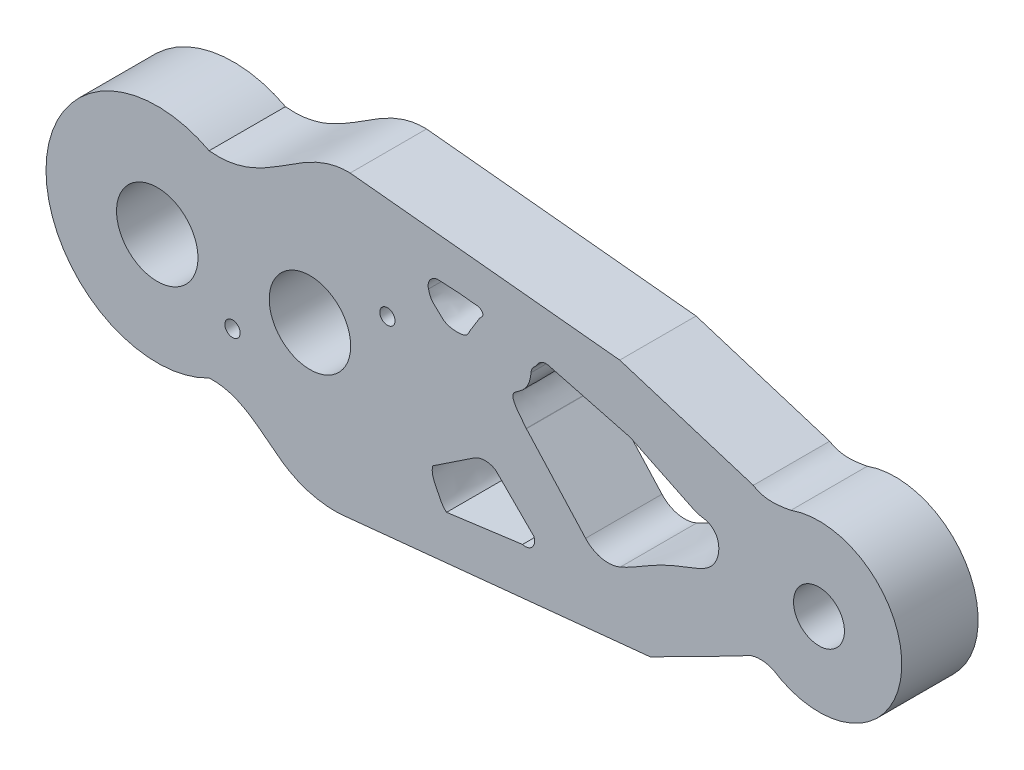
SolidWorks part; units mm, degrees
ref_plane "Front Plane" through (0, 0, 0) normal (0, 0, 1) x (1, 0, 0)
ref_plane "Top Plane" through (0, 0, 0) normal (0, 1, 0) x (1, 0, 0)
ref_plane "Right Plane" through (0, 0, 0) normal (1, 0, 0) x (0, 0, -1)
sketch "Sketch1" plane through (0, 0, 0) normal (0, 0, 1) x (1, 0, 0)
  line L0 (1.3706, 14.9583) -> (51.0041, 9.9495)
  line L1 (1.3706, -14.9583) -> (51.0041, -9.9495)
  line L2 (-15.0209, 15) -> (0, 15.021)
  line L3 (-15, -15) -> (-0.7932, -15)
  circle A0 centre (-15, 0) radius 4
  circle A1 centre (0, 0) radius 4
  circle A2 centre (50, 0) radius 2.5
  arc A4 (-15.0209, 15) -> (-15, -15) centre (-15, 0) ccw
  arc A5 (51.0041, -9.9495) -> (51.0041, 9.9495) centre (50, 0) ccw
  arc A6 (-0.7932, -15) -> (1.3706, -14.9583) centre (0, 0) ccw
  arc A7 (1.3706, 14.9583) -> (0, 15.021) centre (0, 0) ccw
  dimension "D1" = 20
  dimension "D2" = 15
  dimension "D4" = 8
  dimension "D5" = 5
  dimension "D3" = 50
  dimension "D6" = 15
extrude "Boss-Extrude1" add sketch "Sketch1" along normal mid plane 7.5
sketch "Sketch2" plane through (0, 0, 0) normal (0, 0, 1) x (1, 0, 0)
  line L0 (50, -1000) -> (50, 49000) construction
  line L1 (-15, -1000) -> (-15, 49000) construction
sketch "Sketch3" plane through (0, 0, 0) normal (0, 0, 1) x (1, 0, 0)
  line L0 (51.0041, 9.9495) -> (1.3706, 14.9583) construction
  line L1 (1.3706, -14.9583) -> (51.0041, -9.9495) construction
  line L2 (3.9499, 14.698) -> (3.9499, 23.599)
  line L3 (3.9499, 23.599) -> (-33.0984, 23.599)
  line L4 (-33.0984, 23.599) -> (-33.0984, -19.3341)
  line L5 (-33.0984, -19.3341) -> (3.0117, -19.3341)
  line L6 (3.0117, -19.3341) -> (3.0117, -14.7927)
  line L7 (22.5159, 8.3136) -> (31.4696, 5.9632)
  line L8 (31.4696, 5.9632) -> (38.1849, 2.7175)
  line L9 (28.289, -6.1533) -> (21.2552, 1.6112)
  line L10 (12.062, -6.1533) -> (16.0976, -3.4692)
  line L11 (18.2297, -3.4192) -> (21.9757, -7.1651)
  line L12 (13.422, -9.429) -> (20.8814, -8.4313)
  line L13 (11.4379, 10.0141) -> (14.6876, 9.8319)
  line L14 (14.6876, 9.8319) -> (16.2061, 9.6669)
  line L15 (16.7073, 8.7689) -> (15.6746, 7.0985)
  line L16 (30.4292, 12.0258) -> (43.5484, 7.9337)
  line L17 (30.4292, 19.7264) -> (61.7184, 19.7264)
  line L18 (30.4292, 19.7264) -> (30.4292, 12.0258)
  line L19 (30.4292, -17.8524) -> (61.7184, -17.8524)
  line L20 (61.7184, 19.7264) -> (61.7184, -17.8524)
  line L21 (30.4292, -13.2464) -> (42.4049, -7.1651)
  line L22 (30.4292, -13.2464) -> (30.4292, -17.8524)
  arc A0 (-9.9036, 9.6669) -> (-9.9036, -9.6669) centre (-15, 0) ccw
  arc A1 (18.2297, -3.4192) -> (16.0976, -3.4692) centre (17.2032, -5.1314) ccw
  arc A2 (20.8814, -8.4313) -> (21.9757, -7.1651) centre (21.1597, -7.5659) ccw
  arc A3 (45.4924, -6.7727) -> (47.2449, 7.6549) centre (50, 0) ccw
  spline S0 degree 3 poles (-9.9036, 9.6669) (-6.6521, 9.3201) (-2.5752, 12.1807) (1.7399, 14.763) (3.9499, 14.698) knots 0 0 0 0 0.582392 1 1 1 1
  spline S1 degree 3 poles (-9.9036, -9.6669) (-7.4765, -9.5332) (-5.1125, -11.3322) (-1.4199, -14.3078) (1.2483, -14.8931) (3.0117, -14.7927) knots 0 0 0 0 0.454121 0.625344 1 1 1 1
  spline S2 degree 3 poles (38.1849, 2.7175) (40.4644, 2.7256) (40.5673, -0.9319) (37.0228, -2.29) (33.1979, -3.7939) (30.5194, -5.9288) (28.289, -6.1533) knots 0 0 0 0 0.267175 0.422388 0.62445 1 1 1 1
  spline S3 degree 3 poles (21.729, 6.8238) (21.939, 7.3414) (22.4863, 7.3837) (22.5159, 8.3136) knots 0.760302 0.760302 0.760302 0.760302 1 1 1 1
  spline S4 degree 3 poles (21.2552, 1.6112) (18.0975, 5.3327) (21.5612, 3.1493) (21.729, 6.8238) knots 0 0 0 0 1 1 1 1
  spline S5 degree 3 poles (12.062, -6.1533) (11.8801, -6.849) (12.4954, -7.9277) (12.9664, -9.0639) (13.422, -9.429) knots 0 0 0 0 0.534202 1 1 1 1
  spline S6 degree 3 poles (16.2061, 9.6669) (16.6191, 9.734) (17.4081, 9.2716) (16.7073, 8.7689) knots 0 0 0 0 1 1 1 1
  spline S7 degree 3 poles (15.6746, 7.0985) (15.4967, 6.4682) (14.4965, 6.3574) (13.2341, 6.5645) (12.575, 7.3202) (11.8463, 7.9072) (11.593, 8.9011) (11.3809, 9.5826) (11.4379, 10.0141) knots 0 0 0 0 0.243008 0.400784 0.557347 0.677228 0.810823 1 1 1 1
  spline S8 degree 3 poles (43.5484, 7.9337) (44.668, 7.2245) (46.0283, 7.4264) (47.2449, 7.6549) knots 0 0 0 0 1 1 1 1
  spline S9 degree 2 poles (42.4049, -7.1651) (43.7913, -6.1258) (45.4924, -6.7727) knots 0 0 0 1 1 1
extrude "Cut-Extrude1" cut sketch "Sketch3" against normal through all both and the other way through all contours S1 A0 S0 L2 L3 L4 L5 L6 | L12 A2 L11 A1 L10 S5 | S7 L13 L14 S6 L15 | S3 L7 L8 S2 L9 S4 | A3 S8 L16 L18 L17 L20 L19 L22 L21 S9
fillet "Fillet_1mm" radius 1 9 edges at (14.6876, 9.8319, 0) (11.4379, 10.0141, 0) (21.2552, 1.6112, 0) (31.4696, 5.9632, 0) (22.5159, 8.3136, 0) (21.729, 6.8238, 0) (15.6746, 7.0985, 0) (16.7073, 8.7689, 0) (16.2061, 9.6669, 0)
fillet "Fillet_3mm" radius 3 2 edges at (28.289, -6.1533, 0) (38.1849, 2.7175, 0)
sketch "Sketch4" plane through (0, 0, 3.75) normal (0, 0, 1) x (1, 0, 0)
  circle A0 centre (7.6064, 4.325) radius 0.75
  circle A1 centre (-7.6064, -4.325) radius 0.7512
  dimension "D1" = 1.5
  dimension "D2" = 1.5024
extrude "Cut-Extrude2" cut sketch "Sketch4" against normal through all
